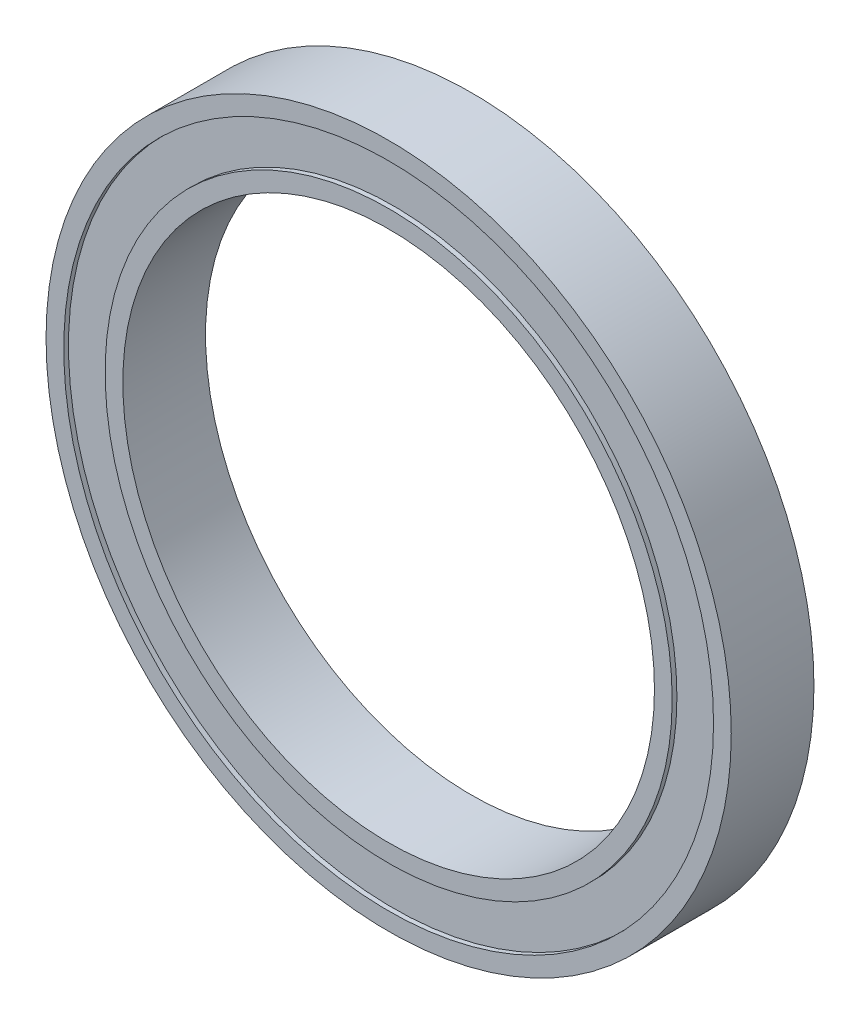
SolidWorks part; units mm, degrees
material "合金钢"
ref_plane "前视基准面" through (0, 0, 0) normal (0, 0, 1) x (1, 0, 0)
ref_plane "上视基准面" through (0, 0, 0) normal (0, 1, 0) x (1, 0, 0)
ref_plane "右视基准面" through (0, 0, 0) normal (1, 0, 0) x (0, 0, -1)
sketch "草图1" plane through (0, 0, 0) normal (0, 0, 1) x (1, 0, 0)
  circle A0 centre (0, 0) radius 22.5
  circle A1 centre (0, 0) radius 29
  dimension "D1" = 45
  dimension "D2" = 58
extrude "凸台-拉伸1" add sketch "草图1" along normal blind 7
sketch "草图2" plane through (0, 0, 7) normal (0, 0, 1) x (1, 0, 0)
  circle A0 centre (0, 0) radius 24
  circle A1 centre (0, 0) radius 27.5
  dimension "D1" = 48
  dimension "D2" = 55
extrude "切除-拉伸1" cut sketch "草图2" against normal blind 0.4
sketch "草图3" plane through (0, 0, 0) normal (0, 0, -1) x (-1, 0, 0)
  circle A0 centre (0, 0) radius 24
  circle A1 centre (0, 0) radius 27.5
  dimension "D1" = 48
  dimension "D2" = 55
extrude "切除-拉伸2" cut sketch "草图3" against normal blind 0.4
